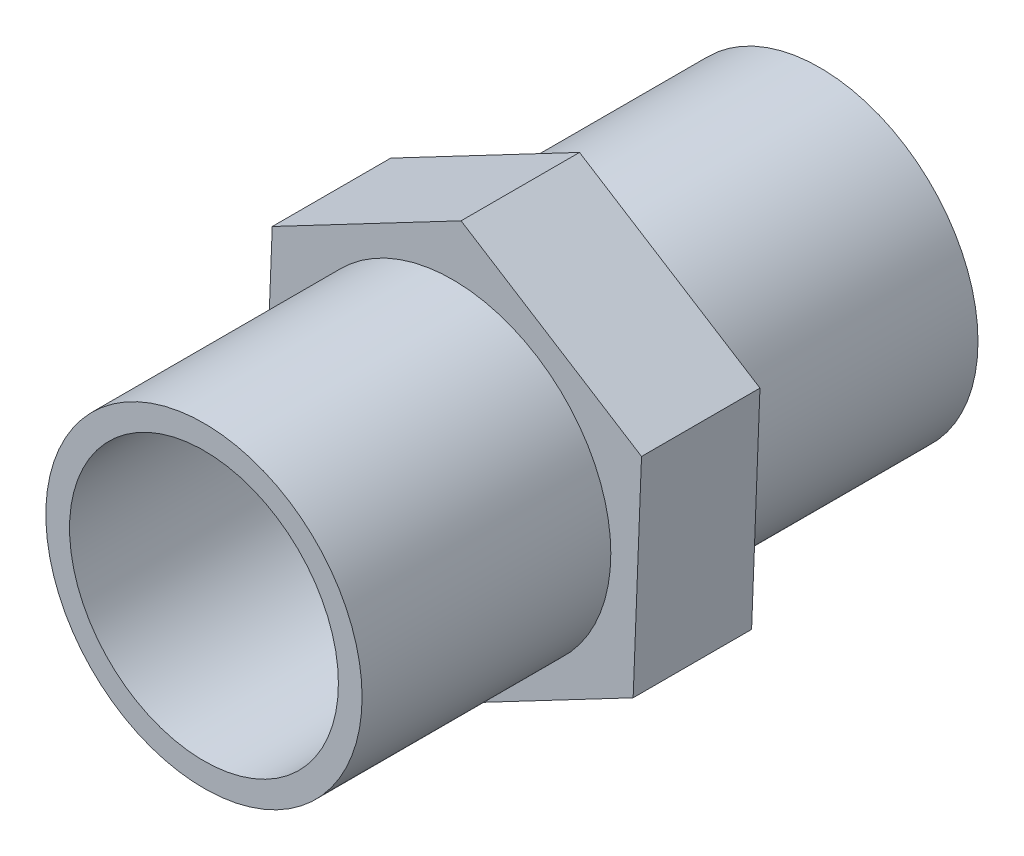
SolidWorks part; units mm, degrees
ref_plane "Front Plane" through (0, 0, 0) normal (0, 0, 1) x (1, 0, 0)
ref_plane "Top Plane" through (0, 0, 0) normal (0, 1, 0) x (1, 0, 0)
ref_plane "Right Plane" through (0, 0, 0) normal (1, 0, 0) x (0, 0, -1)
sketch "Sketch1" plane through (0, 0, 0) normal (0, 0, 1) x (1, 0, 0)
  circle A0 centre (0, 0) radius 13.35
  dimension "D1" = 26.7
extrude "Extrude-Thin1" add sketch "Sketch1" along normal mid plane 52 thin thin type one direction reverse wall 2
sketch "Sketch2" plane through (0, 0, 0) normal (0, 0, 1) x (1, 0, 0)
  line L1 (15.9422, 8.3873) -> (0.7074, 18)
  line L2 (0.7074, 18) -> (-15.2347, 9.6127)
  line L3 (-15.2347, 9.6127) -> (-15.9422, -8.3873)
  line L4 (-15.9422, -8.3873) -> (-0.7074, -18)
  line L5 (-0.7074, -18) -> (15.2347, -9.6127)
  line L6 (15.2347, -9.6127) -> (15.9422, 8.3873)
  circle A0 centre (0, 0) radius 15.6005 construction
  dimension "D1" = 18
extrude "Boss-Extrude1" add sketch "Sketch2" along normal mid plane 10
